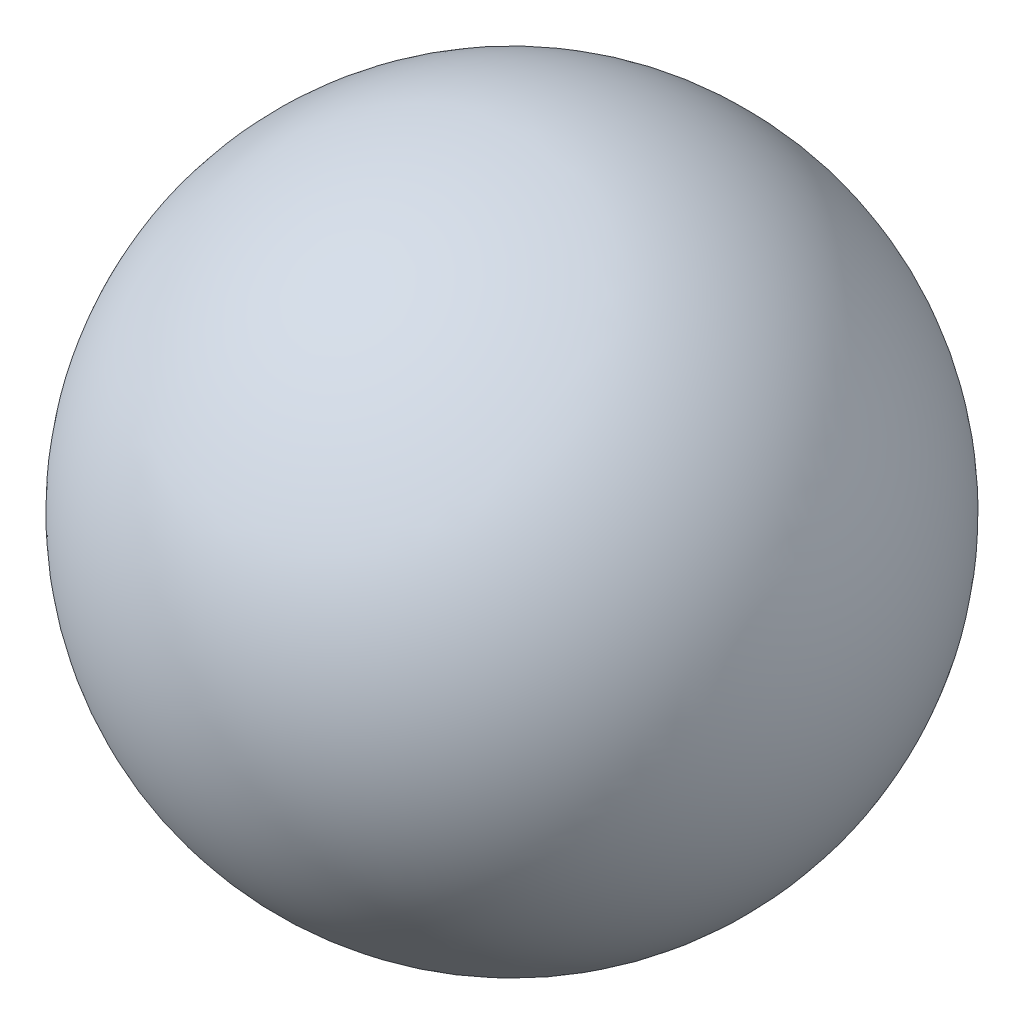
SolidWorks part; units mm, degrees
ref_plane "Front Plane" through (0, 0, 0) normal (0, 0, 1) x (1, 0, 0)
ref_plane "Top Plane" through (0, 0, 0) normal (0, 1, 0) x (1, 0, 0)
ref_plane "Right Plane" through (0, 0, 0) normal (1, 0, 0) x (0, 0, -1)
sketch "Sketch1" plane through (0, 0, 0) normal (0, 0, 1) x (1, 0, 0)
  line L0 (-20.75, 0) -> (20.75, 0)
  arc A0 (20.75, 0) -> (-20.75, 0) centre (0, 0) cw
  dimension "D1" = 41.5
revolve "Revolve1" add sketch "Sketch1" angle 360 about L0
